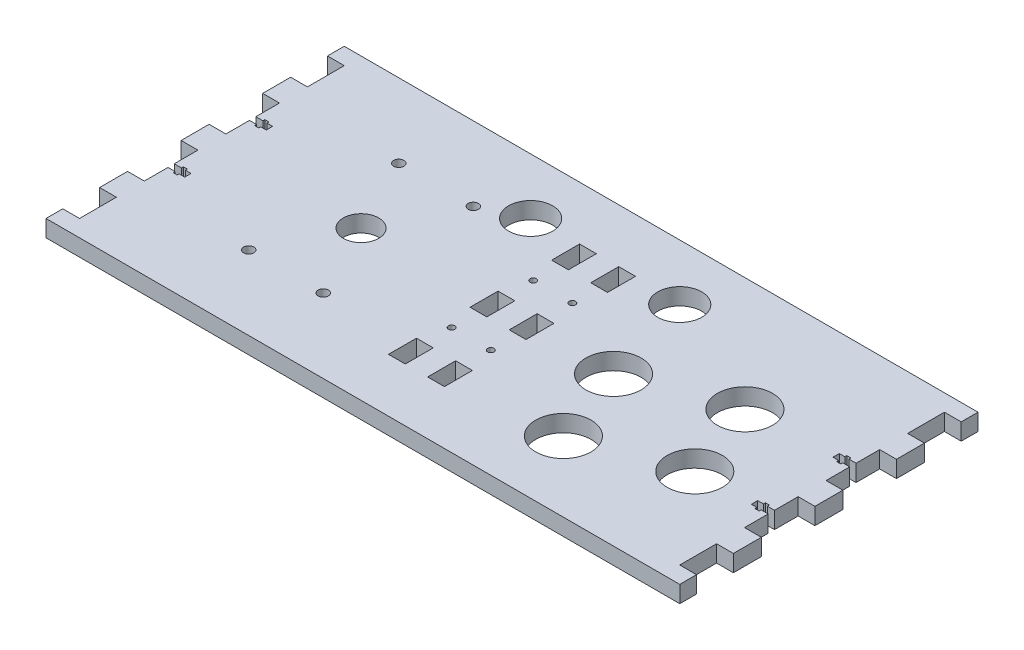
SolidWorks part; units mm, degrees
ref_plane "Front Plane" through (0, 0, 0) normal (0, 0, 1) x (1, 0, 0)
ref_plane "Top Plane" through (0, 0, 0) normal (0, 1, 0) x (1, 0, 0)
ref_plane "Right Plane" through (0, 0, 0) normal (1, 0, 0) x (0, 0, -1)
sketch "Sketch1" plane through (0, 0, 0) normal (0, 1, 0) x (1, 0, 0)
  line L1 (80, -80) -> (-80, -80)
  line L2 (80, -80) -> (80, 80)
  line L3 (80, 80) -> (-80, 80)
  line L4 (-80, -80) -> (-80, 80)
  line L5 (80, -80) -> (-80, 80) construction
  line L6 (80, 80) -> (-80, -80) construction
  point P0 (0, 0)
  dimension "D1" = 160
extrude "Boss-Extrude1" add sketch "Sketch1" along normal blind 9
sketch "Sketch2" plane through (0, 9, 0) normal (0, 1, 0) x (1, 0, 0)
  line L0 (-80, 80) -> (-80, -80) construction
  line L1 (-80, -7.5) -> (-89, -7.5)
  line L2 (-80, -7.5) -> (-80, 7.5)
  line L3 (-80, 7.5) -> (-89, 7.5)
  line L4 (-89, -7.5) -> (-89, 7.5)
  line L5 (-80, 0) -> (0, 0) construction
  line L6 (-80, 80) -> (-80, 51.25) construction
  line L7 (-80, 51.25) -> (-89, 51.25)
  line L8 (-80, 51.25) -> (-80, 36.25)
  line L9 (-80, 36.25) -> (-89, 36.25)
  line L10 (-89, 51.25) -> (-89, 36.25)
  line L11 (-80, -36.25) -> (-89, -36.25)
  line L12 (-80, -36.25) -> (-80, -51.25)
  line L13 (-80, -51.25) -> (-89, -51.25)
  line L14 (-89, -36.25) -> (-89, -51.25)
  line L15 (-80, 36.25) -> (-80, 7.5) construction
  line L16 (-80, -7.5) -> (-80, -36.25) construction
  line L17 (-80, -51.25) -> (-80, -80) construction
  line L19 (-80, 80) -> (-89, 80)
  line L20 (-80, 80) -> (-80, 71)
  line L21 (-80, 71) -> (-89, 71)
  line L22 (-89, 80) -> (-89, 71)
  line L23 (-80, -80) -> (-89, -80)
  line L24 (-80, -80) -> (-80, -71)
  line L25 (-80, -71) -> (-89, -71)
  line L26 (-89, -80) -> (-89, -71)
  dimension "D1" = 9
  dimension "D2" = 15
  dimension "D3" = 9
extrude "Boss-Extrude2" add sketch "Sketch2" against normal up to surface (9 mm away) up to face at (0, 0, 0)
sketch "Sketch3" plane through (0, 9, 0) normal (0, 1, 0) x (1, 0, 0)
  line L1 (75, 51.25) -> (66, 51.25)
  line L2 (75, 51.25) -> (75, 36.25)
  line L3 (75, 36.25) -> (66, 36.25)
  line L4 (66, 51.25) -> (66, 36.25)
  line L5 (-80, 51.25) -> (-89, 51.25) construction
  line L6 (75, 7.5) -> (66, 7.5)
  line L7 (75, 7.5) -> (75, -7.5)
  line L8 (75, -7.5) -> (66, -7.5)
  line L9 (66, 7.5) -> (66, -7.5)
  line L10 (75, -36.25) -> (66, -36.25)
  line L11 (75, -36.25) -> (75, -51.25)
  line L12 (75, -51.25) -> (66, -51.25)
  line L13 (66, -36.25) -> (66, -51.25)
  line L14 (-80, 7.5) -> (-89, 7.5) construction
  line L15 (-89, -7.5) -> (-80, -7.5) construction
  line L16 (-89, -51.25) -> (-80, -51.25) construction
  line L17 (80, -80) -> (80, 80) construction
  line L18 (70.5, 36.25) -> (70.5, 7.5) construction
  line L19 (70.5, 7.5) -> (70.5, -7.5) construction
  line L20 (70.5, -7.5) -> (70.5, -36.25) construction
  line L21 (70.5, -36.25) -> (70.5, -51.25) construction
  line L22 (70.5, -51.25) -> (70.5, -80) construction
  line L23 (-89, -80) -> (80, -80) construction
  line L24 (70.5, 51.25) -> (70.5, 80) construction
  line L25 (80, 80) -> (-89, 80) construction
  circle A0 centre (70.5, 21.875) radius 1.7
  circle A1 centre (70.5, -21.875) radius 1.7
  dimension "D2" = 3.4
  dimension "D1" = 5
extrude "Cut-Extrude1" cut sketch "Sketch3" against normal through all
sketch "Sketch4" plane through (0, 9, 0) normal (0, 1, 0) x (1, 0, 0)
  line L1 (-80, 36.25) -> (-80, 7.5) construction
  line L2 (-89, 51.25) -> (-89, 36.25) construction
  line L3 (-89, 0) -> (0, 0) construction
  line L4 (-89, 7.5) -> (-89, -7.5) construction
  line L5 (-80, -21.875) -> (-71, -21.875) construction
  line L6 (-80, 23.575) -> (-76.2, 23.575)
  line L7 (-80, -23.575) -> (-80, -20.175)
  line L8 (-76.2, -20.175) -> (-80, -20.175)
  line L9 (-76.2, -19.125) -> (-76.2, -20.175)
  line L10 (-74, -19.125) -> (-76.2, -19.125)
  line L11 (-74, -20.175) -> (-74, -19.125)
  line L12 (-71, -20.175) -> (-74, -20.175)
  line L13 (-71, -23.575) -> (-71, -20.175)
  line L14 (-74, -23.575) -> (-71, -23.575)
  line L15 (-74, -24.625) -> (-74, -23.575)
  line L16 (-76.2, -24.625) -> (-74, -24.625)
  line L17 (-76.2, -23.575) -> (-76.2, -24.625)
  line L18 (-80, -23.575) -> (-76.2, -23.575)
  line L20 (-76.2, 23.575) -> (-76.2, 24.625)
  line L21 (-76.2, 24.625) -> (-74, 24.625)
  line L22 (-74, 24.625) -> (-74, 23.575)
  line L23 (-74, 23.575) -> (-71, 23.575)
  line L24 (-71, 23.575) -> (-71, 20.175)
  line L25 (-71, 20.175) -> (-74, 20.175)
  line L26 (-74, 20.175) -> (-74, 19.125)
  line L27 (-74, 19.125) -> (-76.2, 19.125)
  line L28 (-76.2, 19.125) -> (-76.2, 20.175)
  line L29 (-76.2, 20.175) -> (-80, 20.175)
  line L30 (-80, 23.575) -> (-80, 20.175)
  line L31 (-80, 21.875) -> (-71, 21.875) construction
  dimension "D1" = 3.4
  dimension "D2" = 18
  dimension "D3" = 2.2
  dimension "D4" = 5.5
  dimension "D5" = 3
extrude "Cut-Extrude2" cut sketch "Sketch4" against normal through all
sketch "Sketch5" plane through (0, 9, 0) normal (0, 1, 0) x (1, 0, 0)
  line L0 (-22.75, 40.25) -> (-22.75, -40.25) construction
  line L5 (20, -40.25) -> (-20, 40.25) construction
  line L6 (20, 40.25) -> (-20, -40.25) construction
  line L7 (-20, 43) -> (20, 43) construction
  line L8 (22.75, 40.25) -> (22.75, -40.25) construction
  line L9 (-20, -43) -> (20, -43) construction
  circle A0 centre (0, 0) radius 9.5
  circle A1 centre (-20, 40.25) radius 2.75
  circle A2 centre (20, 40.25) radius 2.75
  circle A3 centre (20, -40.25) radius 2.75
  circle A4 centre (-20, -40.25) radius 2.75
  dimension "D1" = 19
  dimension "D2" = 5.5
  dimension "D3" = 45.5
  dimension "D4" = 86
extrude "Cut-Extrude3" cut sketch "Sketch5" against normal through all
sketch "Sketch6" plane through (80, 0, 0) normal (1, 0, 0) x (0, 0, -1)
  line L4 (-80, 0) -> (80, 0)
  line L5 (80, 0) -> (80, 9)
  line L6 (80, 9) -> (-80, 9)
  line L7 (-80, 9) -> (-80, 0)
  line L8 (-80, 0) -> (80, 0)
  line L9 (80, 0) -> (80, 9)
  line L10 (80, 9) -> (-80, 9)
  line L11 (-80, 9) -> (-80, 0)
  dimension "D1" = 0
extrude "Boss-Extrude3" add sketch "Sketch6" along normal up to surface (1 mm away)
sketch "Sketch7" plane through (0, 9, 0) normal (0, 1, 0) x (1, 0, 0)
  line L1 (81, 80) -> (41, 80) construction
  line L2 (81, 80) -> (81, 50) construction
  line L3 (81, 50) -> (41, 50) construction
  line L4 (41, 80) -> (41, 50) construction
  circle A0 centre (41, 50) radius 11.8
  dimension "D1" = 23.6
  dimension "D2" = 30
  dimension "D3" = 40
extrude "Cut-Extrude4" cut sketch "Sketch7" against normal through all
mirror "Mirror1" about plane through (81, 0, 0) normal (-1, 0, 0) of "Cut-Extrude4", "Boss-Extrude3", "Cut-Extrude2", "Boss-Extrude2", "Boss-Extrude1", "Cut-Extrude1"
sketch "Sketch8" plane through (0, 9, 0) normal (0, 1, 0) x (1, 0, 0)
  line L0 (135.463, 0) -> (150.8539, -42.2862) construction
  line L1 (135.463, 0) -> (187.1461, 18.8111) construction
  line L2 (150.8539, -42.2862) -> (202.537, -23.4751) construction
  line L3 (187.1461, 18.8111) -> (202.537, -23.4751) construction
  line L4 (135.463, 0) -> (202.537, -23.4751) construction
  line L5 (150.8539, -42.2862) -> (187.1461, 18.8111) construction
  line L6 (0, 0) -> (169, 0) construction
  line L7 (169, 0) -> (169, -11.7375) construction
  line L8 (242, 51.25) -> (242, 36.25) construction
  line L9 (242, 43.75) -> (96, 43.75) construction
  line L10 (96, 51.25) -> (96, 36.25) construction
  line L11 (169, 43.75) -> (169, 0) construction
  circle A0 centre (135.463, 0) radius 14.825
  circle A1 centre (187.1461, 18.8111) radius 14.825
  circle A2 centre (202.537, -23.4751) radius 14.825
  circle A3 centre (150.8539, -42.2862) radius 14.825
  point P1 (169, -11.7375)
  dimension "D1" = 29.65
  dimension "D2" = 20
  dimension "D3" = 45
  dimension "D4" = 55
extrude "Cut-Extrude5" cut sketch "Sketch8" against normal through all
